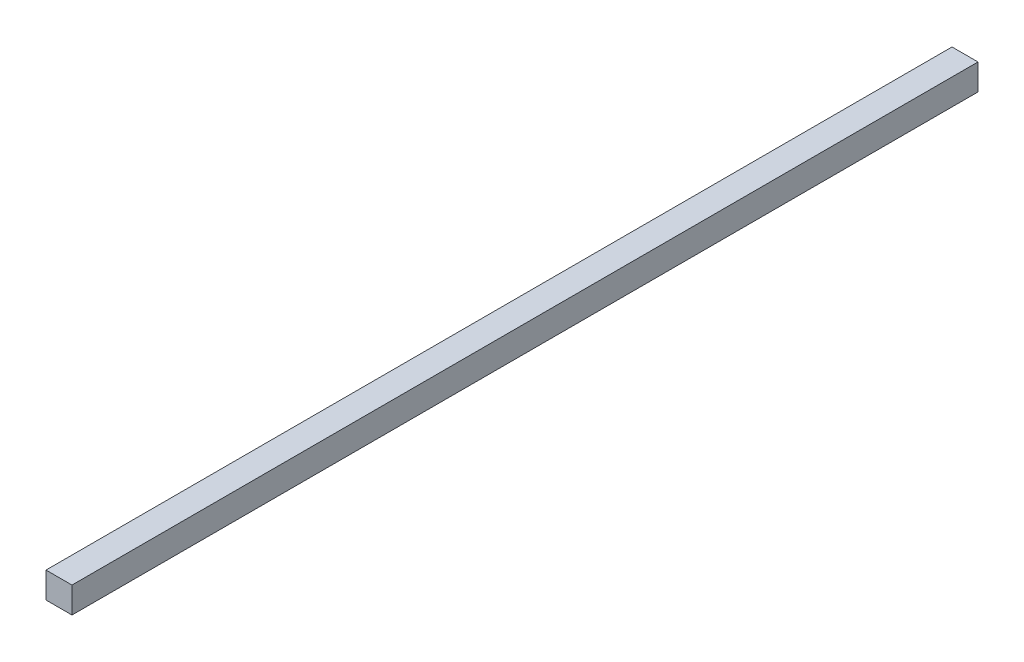
SolidWorks part; units mm, degrees
ref_plane "Front Plane" through (0, 0, 0) normal (0, 0, 1) x (1, 0, 0)
ref_plane "Top Plane" through (0, 0, 0) normal (0, 1, 0) x (1, 0, 0)
ref_plane "Right Plane" through (0, 0, 0) normal (1, 0, 0) x (0, 0, -1)
sketch "Sketch1" plane through (0, 0, 0) normal (0, 0, 1) x (1, 0, 0)
  line L1 (-1.4338, -1.4338) -> (1.4338, -1.4338)
  line L2 (-1.4338, -1.4338) -> (-1.4338, 1.4338)
  line L3 (-1.4338, 1.4338) -> (1.4338, 1.4338)
  line L4 (1.4338, -1.4338) -> (1.4338, 1.4338)
  line L5 (-1.4338, -1.4338) -> (1.4338, 1.4338) construction
  line L6 (-1.4338, 1.4338) -> (1.4338, -1.4338) construction
  point P0 (0, 0)
  dimension "D1" = 2.8676
extrude "Boss-Extrude1" add sketch "Sketch1" along normal blind 100
